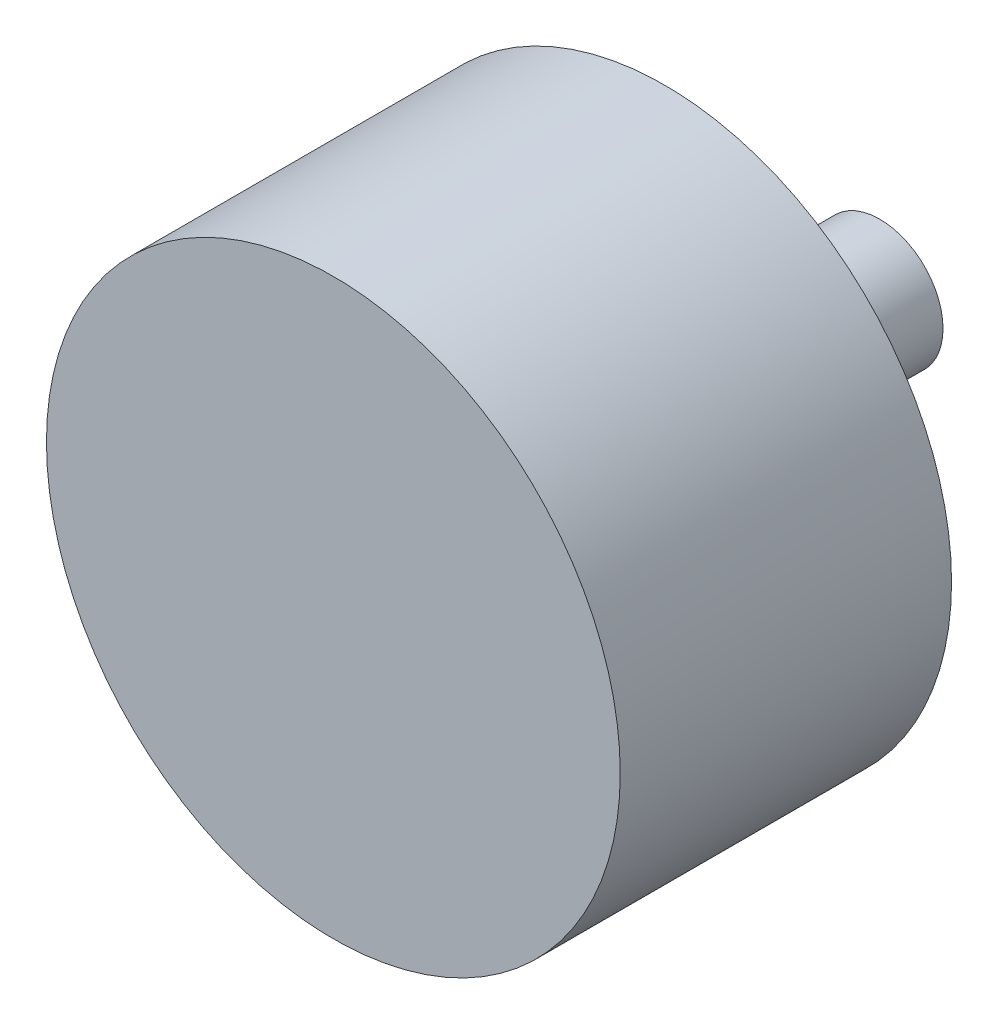
SolidWorks part; units mm, degrees
ref_plane "Front Plane" through (0, 0, 0) normal (0, 0, 1) x (1, 0, 0)
ref_plane "Top Plane" through (0, 0, 0) normal (0, 1, 0) x (1, 0, 0)
ref_plane "Right Plane" through (0, 0, 0) normal (1, 0, 0) x (0, 0, -1)
sketch "Sketch1" plane through (0, 0, 0) normal (1, 0, 0) x (0, 0, -1)
  line L0 (0, 0) -> (53.4361, 0) construction
  line L1 (0, 0) -> (0, 21.336)
  line L2 (0, 21.336) -> (24.638, 21.336)
  line L3 (24.638, 21.336) -> (24.638, 5.461)
  line L4 (24.638, 5.461) -> (30.48, 5.461)
  line L5 (30.48, 5.461) -> (30.48, 4.699)
  line L6 (30.48, 4.699) -> (40.64, 4.699)
  line L7 (40.64, 4.699) -> (40.64, 0)
  line L8 (0, 0) -> (40.64, 0)
  dimension "D1" = 40.64
  dimension "D2" = 42.672
  dimension "D3" = 10.922
  dimension "D4" = 9.398
  dimension "D5" = 5.842
  dimension "D6" = 24.638
revolve "Revolve1" add sketch "Sketch1" angle 360 about L0
